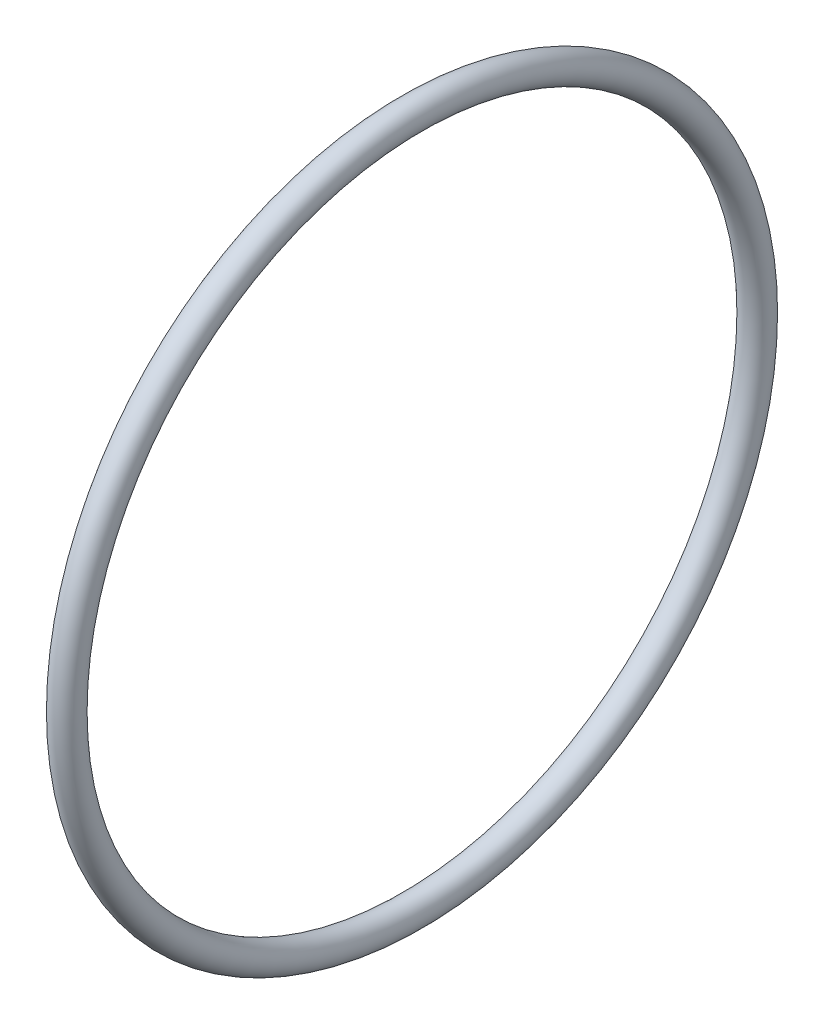
SolidWorks part; units mm, degrees
material "BUTYL"
ref_plane "Alzado" through (0, 0, 0) normal (0, 0, 1) x (1, 0, 0)
ref_plane "Planta" through (0, 0, 0) normal (0, 1, 0) x (1, 0, 0)
ref_plane "Vista lateral" through (0, 0, 0) normal (1, 0, 0) x (0, 0, -1)
sketch "Croquis1" plane through (0, 0, 0) normal (0, 0, 1) x (1, 0, 0)
  line L0 (0, 0) -> (28.345, 0) construction
  circle A0 centre (0, 48) radius 2
  dimension "D1" = 4
  dimension "D2" = 50
revolve "Revolución1" add sketch "Croquis1" angle 360 about L0
